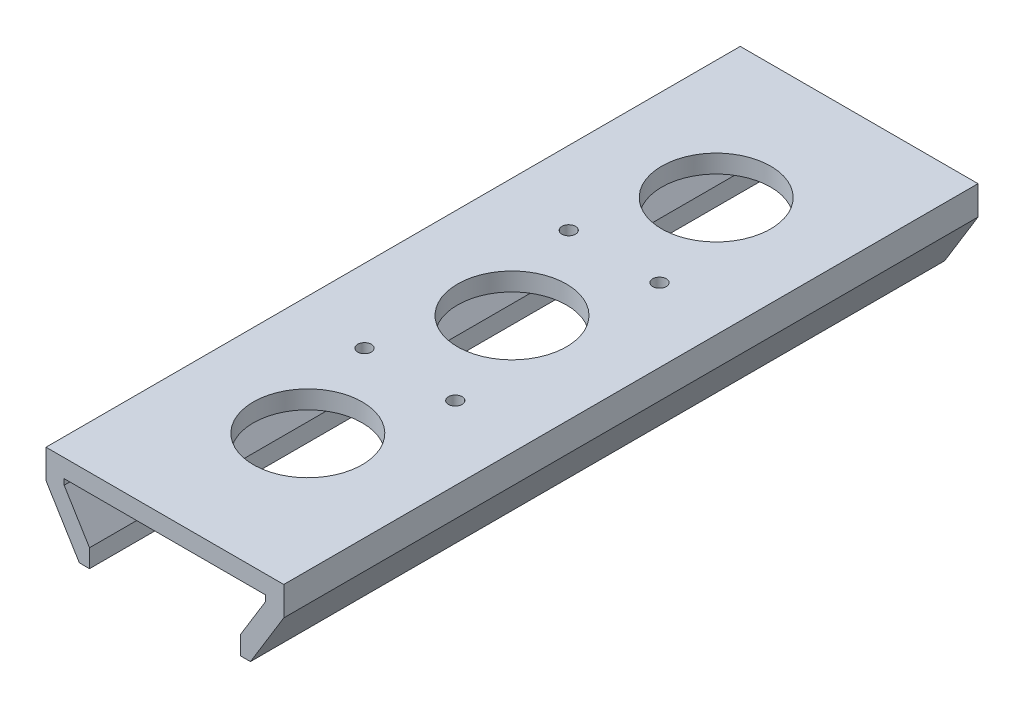
SolidWorks part; units mm, degrees
ref_plane "Płaszczyzna przednia" through (0, 0, 0) normal (0, 0, 1) x (1, 0, 0)
ref_plane "Płaszczyzna górna" through (0, 0, 0) normal (0, 1, 0) x (1, 0, 0)
ref_plane "Płaszczyzna prawa" through (0, 0, 0) normal (1, 0, 0) x (0, 0, -1)
sketch "Sketch1" plane through (0, 0, 0) normal (0, 0, 1) x (1, 0, 0)
  line L0 (0, -13.2894) -> (0, -81.2091) construction
  line L1 (0, -13.4894) -> (22, -13.4894)
  line L2 (22, -13.4894) -> (22, -14.4894)
  line L3 (16.5, -23.4894) -> (0, -23.4894)
  line L4 (22, -14.4894) -> (16.5, -23.4894)
  line L5 (0, -13.4894) -> (0, -23.4894)
  line L6 (0, -13.2894) -> (22.2, -13.2894)
  line L7 (22.2, -13.2894) -> (22.2, -14.5456)
  line L8 (22.2, -14.5456) -> (16.6122, -23.6894)
  line L9 (16.6122, -23.6894) -> (0, -23.6894)
  line L11 (18.8555, -27.6894) -> (16.6122, -27.6894)
  line L13 (-26.2, -9.2894) -> (26.2, -9.2894)
  line L14 (26.2, -9.2894) -> (26.2, -15.6711)
  line L15 (26.2, -15.6711) -> (18.8555, -27.6894)
  line L16 (0, -13.2894) -> (0, -31.461)
  line L17 (16.6122, -23.6894) -> (16.6122, -27.6894)
  line L18 (-4.2, -9.2894) -> (-4.2, -27.6894) construction
  line L20 (-4.2, -9.2894) -> (26.2, -9.2894) construction
  line L21 (18.8555, -27.6894) -> (-4.2, -27.6894) construction
  line L22 (-0.2, -13.2894) -> (-0.2, -23.6894) construction
  line L23 (16.6122, -23.6894) -> (-0.2, -23.6894) construction
  line L24 (-0.2, -13.2894) -> (22.2, -13.2894) construction
  line L25 (-26.2, -9.2894) -> (-26.2, -15.6711)
  line L26 (-26.2, -15.6711) -> (-18.8555, -27.6894)
  line L27 (-18.8555, -27.6894) -> (-16.6122, -27.6894)
  line L28 (-16.6122, -23.6894) -> (-16.6122, -27.6894)
  line L29 (-22.2, -14.5456) -> (-16.6122, -23.6894)
  line L30 (-22.2, -13.2894) -> (-22.2, -14.5456)
  line L31 (0, -13.2894) -> (-22.2, -13.2894)
  point P4 (22, -23.4894)
  dimension "D1" = 9
  dimension "D2" = 5.5
  dimension "D3" = 10
  dimension "D4" = 22
  dimension "D5" = 0.2
  dimension "D6" = 4
extrude "Boss-Extrude1" add sketch "Sketch1" along normal blind 153 contours L31 L6 L7 L8 L17 L11 L15 L14 L13 L25 L26 L27 L28 L29 L30
sketch "Sketch2" plane through (0, -9.2894, 0) normal (0, 1, 0) x (1, 0, 0)
  line L0 (0, 0) -> (0, -186.0262) construction
  circle A0 centre (0, -31.5) radius 12
  circle A1 centre (0, -76.5) radius 12
  circle A2 centre (0, -121.5) radius 12
  dimension "D2" = 24
  dimension "D1" = 186.0262
  dimension "D3" = 31.5
  dimension "D5" = 45
  dimension "D4" = 3
extrude "Cut-Extrude1" cut sketch "Sketch2" against normal blind 213
sketch "Sketch3" plane through (0, -9.2894, 0) normal (0, 1, 0) x (1, 0, 0)
  line L0 (-41.0874, -76.5) -> (42.5248, -76.5) construction
  line L1 (0, -76.5) -> (0, -121.5) construction
  line L2 (-10, -99) -> (10, -99) construction
  line L3 (-10, -54) -> (10, -54) construction
  circle A0 centre (0, -76.5) radius 12
  circle A1 centre (0, -76.5) radius 12 construction
  circle A2 centre (0, -121.5) radius 12
  circle A3 centre (0, -121.5) radius 12 construction
  circle A4 centre (-10, -99) radius 1.5
  circle A5 centre (10, -99) radius 1.5
  circle A6 centre (10, -54) radius 1.5
  circle A7 centre (-10, -54) radius 1.5
  point P9 (0, -99)
  point P18 (0, -99)
  dimension "D2" = 3
  dimension "D1" = 20
extrude "Cut-Extrude2" cut sketch "Sketch3" against normal blind 10 contours A5 | A4 | A7 | A6
